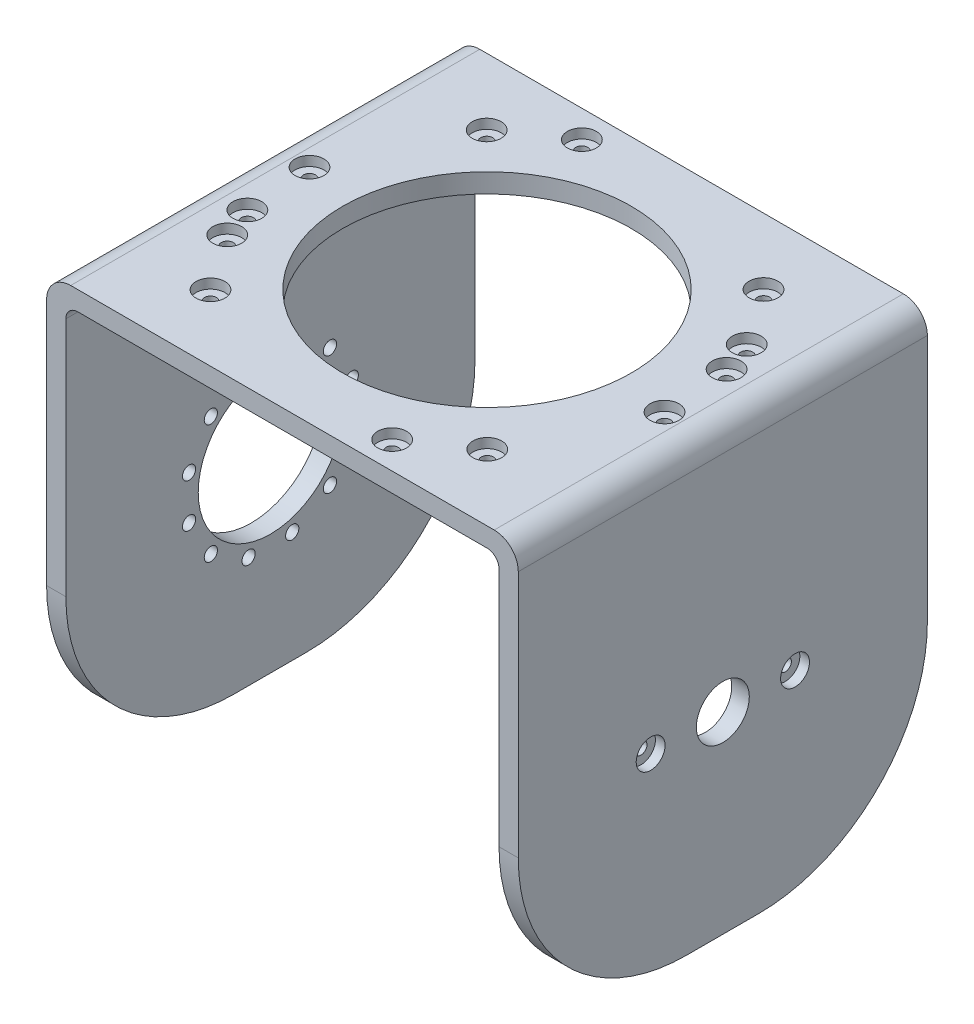
SolidWorks part; units mm, degrees
material "6061 合金"
ref_plane "前视基准面" through (0, 0, 0) normal (0, 0, 1) x (1, 0, 0)
ref_plane "上视基准面" through (0, 0, 0) normal (0, 1, 0) x (1, 0, 0)
ref_plane "右视基准面" through (0, 0, 0) normal (1, 0, 0) x (0, 0, -1)
other "Configuration Table"
sketch "草图1" plane through (0, 0, 0) normal (0, 0, 1) x (1, 0, 0)
  line L0 (-180, 0) -> (0, 0)
  line L1 (0, 0) -> (0, -175)
  line L3 (8, -175) -> (8, 8)
  line L4 (8, 8) -> (-180, 8)
  line L6 (0, -175) -> (8, -175)
  line L12 (-180, 8) -> (-188, 8)
  line L13 (-180, 0) -> (-180, -175)
  line L14 (-180, -175) -> (-188, -175)
  line L15 (-188, 8) -> (-188, -175)
  dimension "D1" = 8
  dimension "D2" = 8
  dimension "D4" = 180
  dimension "D5" = 183
  dimension "D6" = 8
  dimension "D8" = 8
extrude "凸台-拉伸1" add sketch "草图1" along normal blind 170
sketch "草图2" plane through (0, 8, 0) normal (0, 1, 0) x (1, 0, 0)
  line L0 (-216.3195, -85) -> (51.5119, -85) construction
  line L1 (8, -170) -> (-188, -170) construction
  line L2 (8, 0) -> (-188, 0) construction
  line L7 (-90, -75.3242) -> (-90, -92.2023) construction
  line L8 (8, -170) -> (8, 0) construction
  line L9 (-188, -170) -> (-188, 0) construction
  circle A2 centre (-90, -85) radius 60
  dimension "D3" = 120
extrude "切除-拉伸1" cut sketch "草图2" against normal blind 180 contours A2 L0 | L0 A2
sketch "草图3" plane through (8, 0, 0) normal (1, 0, 0) x (0, 0, -1)
  line L0 (-85, 25.6845) -> (-85, -173.3318) construction
  line L1 (0, -175) -> (0, 8) construction
  line L2 (-170, -175) -> (-170, 8) construction
  line L3 (-170, -175) -> (0, -175) construction
  line L4 (0, 0) -> (-209.686, 0) construction
  circle A0 centre (-85, -95) radius 11
  dimension "D1" = 22
  dimension "D2" = 80
extrude "切除-拉伸2" cut sketch "草图3" against normal through all both and the other way through all contours A0
fillet "圆角1" radius 70 4 edges at (-184, -175, 170) (-184, -175, 0) (4, -175, 0) (4, -175, 170)
fillet "圆角2" radius 5 2 edges at (-180, 0, 85) (0, 0, 85)
fillet "圆角3" radius 10 2 edges at (8, 8, 85) (-188, 8, 85)
sketch "草图6" plane through (-188, 0, 0) normal (-1, 0, 0) x (0, 0, 1)
  circle A0 centre (85, -95) radius 30
  dimension "D1" = 60
extrude "切除-拉伸6" cut sketch "草图6" against normal blind 39
sketch "草图7" plane through (0, 0, 0) normal (-1, 0, 0) x (0, 0, 1)
  circle A0 centre (85, -95) radius 13
  dimension "D1" = 26
extrude "切除-拉伸7" cut sketch "草图7" against normal blind 0.7
sketch "草图8" plane through (8, 0, 0) normal (1, 0, 0) x (0, 0, -1)
  line L0 (-85, -95) -> (-13.3452, -95) construction
  line L1 (-85, -95) -> (-143.0331, -95) construction
  circle A0 centre (-55, -95) radius 2.5
  circle A1 centre (-115, -95) radius 2.5
  dimension "D1" = 5
  dimension "D2" = 5
  dimension "D3" = 30
  dimension "D4" = 30
extrude "切除-拉伸8" cut sketch "草图8" against normal blind 10
sketch "草图9" plane through (8, 0, 0) normal (1, 0, 0) x (0, 0, -1)
  circle A0 centre (-55, -95) radius 6
  circle A1 centre (-115, -95) radius 6
  dimension "D1" = 12
  dimension "D2" = 12
extrude "切除-拉伸9" cut sketch "草图9" against normal blind 4
sketch "草图10" plane through (0, 0, 0) normal (0, -1, 0) x (1, 0, 0)
  arc A0 (-173.1989, 76.7742) -> (-168.6673, 78.8872) centre (-170.9331, 77.8307) ccw construction
  arc A1 (-149.7806, 26.5535) -> (-145.249, 28.6665) centre (-147.5148, 27.61) ccw construction
  arc A2 (-126.5235, 10.2687) -> (-121.992, 12.3818) centre (-124.2577, 11.3252) ccw construction
  arc A3 (-113.38, 5.4849) -> (-108.8485, 7.598) centre (-111.1143, 6.5414) ccw construction
  arc A4 (-85.0965, 3.0104) -> (-80.5649, 5.1235) centre (-82.8307, 4.0669) ccw construction
  arc A5 (-34.8758, 26.4287) -> (-30.3442, 28.5418) centre (-32.61, 27.4852) ccw construction
  arc A6 (-13.8072, 62.8292) -> (-9.2756, 64.9423) centre (-11.5414, 63.8857) ccw construction
  arc A7 (-18.591, 49.6857) -> (-14.0595, 51.7988) centre (-16.3252, 50.7423) ccw construction
  arc A8 (-6.8011, 93.2258) -> (-11.3327, 91.1128) centre (-9.0669, 92.1693) ccw construction
  arc A9 (-30.2194, 143.4465) -> (-34.751, 141.3335) centre (-32.4852, 142.39) ccw construction
  arc A10 (-53.4765, 159.7313) -> (-58.008, 157.6182) centre (-55.7423, 158.6748) ccw construction
  arc A11 (-66.62, 164.5151) -> (-71.1515, 162.402) centre (-68.8857, 163.4586) ccw construction
  arc A12 (-94.9035, 166.9896) -> (-99.4351, 164.8765) centre (-97.1693, 165.9331) ccw construction
  arc A13 (-145.1242, 143.5713) -> (-149.6558, 141.4582) centre (-147.39, 142.5148) ccw construction
  arc A14 (-161.409, 120.3143) -> (-165.9405, 118.2012) centre (-163.6748, 119.2577) ccw construction
  arc A15 (-166.1928, 107.1708) -> (-170.7244, 105.0577) centre (-168.4586, 106.1143) ccw construction
  arc A16 (-173.1989, 76.7742) -> (-168.6673, 78.8872) centre (-170.9331, 77.8307) ccw construction
  arc A17 (-149.7806, 26.5535) -> (-145.249, 28.6665) centre (-147.5148, 27.61) ccw construction
  arc A18 (-126.5235, 10.2687) -> (-121.992, 12.3818) centre (-124.2577, 11.3252) ccw construction
  arc A19 (-113.38, 5.4849) -> (-108.8485, 7.598) centre (-111.1143, 6.5414) ccw construction
  arc A20 (-85.0965, 3.0104) -> (-80.5649, 5.1235) centre (-82.8307, 4.0669) ccw construction
  arc A21 (-34.8758, 26.4287) -> (-30.3442, 28.5418) centre (-32.61, 27.4852) ccw construction
  arc A22 (-13.8072, 62.8292) -> (-9.2756, 64.9423) centre (-11.5414, 63.8857) ccw construction
  arc A23 (-18.591, 49.6857) -> (-14.0595, 51.7988) centre (-16.3252, 50.7423) ccw construction
  arc A24 (-6.8011, 93.2258) -> (-11.3327, 91.1128) centre (-9.0669, 92.1693) ccw construction
  arc A25 (-30.2194, 143.4465) -> (-34.751, 141.3335) centre (-32.4852, 142.39) ccw construction
  arc A26 (-53.4765, 159.7313) -> (-58.008, 157.6182) centre (-55.7423, 158.6748) ccw construction
  arc A27 (-66.62, 164.5151) -> (-71.1515, 162.402) centre (-68.8857, 163.4586) ccw construction
  arc A28 (-94.9035, 166.9896) -> (-99.4351, 164.8765) centre (-97.1693, 165.9331) ccw construction
  arc A29 (-145.1242, 143.5713) -> (-149.6558, 141.4582) centre (-147.39, 142.5148) ccw construction
  arc A30 (-161.409, 120.3143) -> (-165.9405, 118.2012) centre (-163.6748, 119.2577) ccw construction
  arc A31 (-166.1928, 107.1708) -> (-170.7244, 105.0577) centre (-168.4586, 106.1143) ccw construction
  circle A32 centre (-32.4852, 142.39) radius 2.5
  circle A33 centre (-55.7423, 158.6748) radius 2.5
  circle A34 centre (-68.8857, 163.4586) radius 2.5
  circle A35 centre (-147.39, 142.5148) radius 2.5
  circle A36 centre (-163.6748, 119.2577) radius 2.5
  circle A37 centre (-168.4586, 106.1143) radius 2.5
  circle A38 centre (-170.9331, 77.8307) radius 2.5
  circle A40 centre (-147.5148, 27.61) radius 2.5
  circle A41 centre (-124.2577, 11.3252) radius 2.5
  circle A42 centre (-111.1143, 6.5414) radius 2.5
  circle A44 centre (-32.61, 27.4852) radius 2.5
  circle A45 centre (-16.3252, 50.7423) radius 2.5
  circle A46 centre (-11.5414, 63.8857) radius 2.5
  circle A47 centre (-9.0669, 92.1693) radius 2.5
  dimension "D1" = 5
extrude "切除-拉伸10" cut sketch "草图10" against normal blind 10 contours A33 | A32 | A47 | A46 | A45 | A44 | A41 | A40 | A38 | A37 | A36 | A35
sketch "草图11" plane through (0, 8, 0) normal (0, 1, 0) x (1, 0, 0)
  circle A1 centre (-32.61, -27.4852) radius 6
  circle A2 centre (-16.3252, -50.7423) radius 6
  circle A3 centre (-11.5414, -63.8857) radius 6
  circle A4 centre (-9.0669, -92.1693) radius 6
  circle A5 centre (-32.4852, -142.39) radius 6
  circle A6 centre (-55.7423, -158.6748) radius 6
  circle A8 centre (-147.39, -142.5148) radius 6
  circle A9 centre (-163.6748, -119.2577) radius 6
  circle A10 centre (-168.4586, -106.1143) radius 6
  circle A11 centre (-170.9331, -77.8307) radius 6
  circle A12 centre (-147.5148, -27.61) radius 6
  circle A13 centre (-124.2577, -11.3252) radius 6
  circle M2 centre (-55.7423, -158.6748) radius 2.5
  circle M4 centre (-147.39, -142.5148) radius 2.5
  circle M5 centre (-163.6748, -119.2577) radius 2.5
  circle M6 centre (-168.4586, -106.1143) radius 2.5
  circle M7 centre (-170.9331, -77.8307) radius 2.5
  circle M8 centre (-147.5148, -27.61) radius 2.5
  circle M9 centre (-124.2577, -11.3252) radius 2.5
  circle M11 centre (-32.61, -27.4852) radius 2.5
  circle M12 centre (-16.3252, -50.7423) radius 2.5
  circle M13 centre (-11.5414, -63.8857) radius 2.5
  circle M14 centre (-9.0669, -92.1693) radius 2.5
  circle M15 centre (-32.4852, -142.39) radius 2.5
  dimension "D1" = 12
extrude "切除-拉伸11" cut sketch "草图11" against normal blind 4 contours A5 M15 | A6 M2 | A8 M4 | A9 M5 | A10 M6 | A11 M7 | A12 M8 | A13 M9 | A1 M11 | A2 M12 | A3 M13 | A4 M14
sketch "草图12" plane through (-188, 0, 0) normal (-1, 0, 0) x (0, 0, 1)
  line L0 (85, -95) -> (85, -143.8801) construction
  line L1 (85, -95) -> (97.9809, -143.4455) construction
  circle A0 centre (94.0587, -128.8074) radius 2.75
  circle A1 centre (75.9413, -128.8074) radius 2.75
  circle A2 centre (60.2513, -119.7487) radius 2.75
  circle A3 centre (51.1926, -104.0587) radius 2.75
  circle A4 centre (51.1926, -85.9413) radius 2.75
  circle A5 centre (60.2513, -70.2513) radius 2.75
  circle A6 centre (75.9413, -61.1926) radius 2.75
  circle A7 centre (94.0587, -61.1926) radius 2.75
  circle A8 centre (109.7487, -70.2513) radius 2.75
  circle A9 centre (118.8074, -85.9413) radius 2.75
  circle A10 centre (118.8074, -104.0587) radius 2.75
  circle A11 centre (109.7487, -119.7487) radius 2.75
  point P31 (85, -95)
  dimension "D2" = 5.5
  dimension "D1" = 15
  dimension "D3" = 35
  dimension "D4" = 12
extrude "切除-拉伸12" cut sketch "草图12" against normal blind 10
